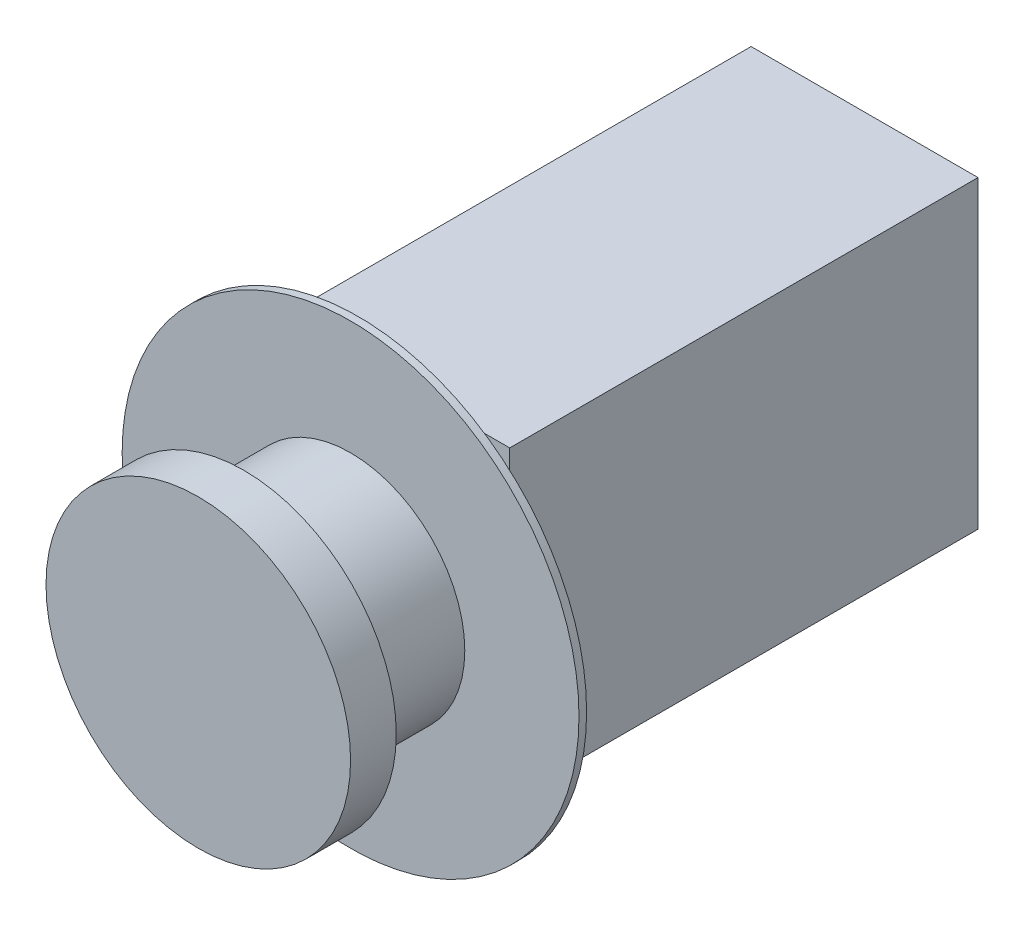
SolidWorks part; units mm, degrees
ref_plane "Front Plane" through (0, 0, 0) normal (0, 0, 1) x (1, 0, 0)
ref_plane "Top Plane" through (0, 0, 0) normal (0, 1, 0) x (1, 0, 0)
ref_plane "Right Plane" through (0, 0, 0) normal (1, 0, 0) x (0, 0, -1)
sketch "Sketch1" plane through (0, 0, 0) normal (0, 0, 1) x (1, 0, 0)
  circle A0 centre (0, 0) radius 15
  dimension "D1" = 30
extrude "Boss-Extrude1" add sketch "Sketch1" along normal blind 15
sketch "Sketch2" plane through (0, 0, 15) normal (0, 0, 1) x (1, 0, 0)
  circle A0 centre (0, 0) radius 20
  dimension "D1" = 40
extrude "Boss-Extrude2" add sketch "Sketch2" along normal blind 6
sketch "Sketch3" plane through (0, 0, 0) normal (0, 0, -1) x (-1, 0, 0)
  circle A0 centre (0, 0) radius 11
  dimension "D1" = 22
extrude "Boss-Extrude3" add sketch "Sketch3" along normal blind 15
sketch "Sketch4" plane through (0, 0, 0) normal (0, 0, -1) x (-1, 0, 0)
  line L1 (-14.9, 20) -> (14.9, 20)
  line L2 (-14.9, 20) -> (-14.9, -20)
  line L3 (-14.9, -20) -> (14.9, -20)
  line L4 (14.9, 20) -> (14.9, -20)
  line L5 (-14.9, 20) -> (14.9, -20) construction
  line L6 (-14.9, -20) -> (14.9, 20) construction
  point P0 (0, 0)
  dimension "D1" = 29.8
  dimension "D2" = 40
extrude "Boss-Extrude4" add sketch "Sketch4" along normal blind 61.5 from offset 5
sketch "Sketch5" plane through (0, 0, 0) normal (0, 0, -1) x (-1, 0, 0)
  circle A0 centre (0, 0) radius 30
  dimension "D1" = 60
extrude "Boss-Extrude5" add sketch "Sketch5" against normal blind 1
